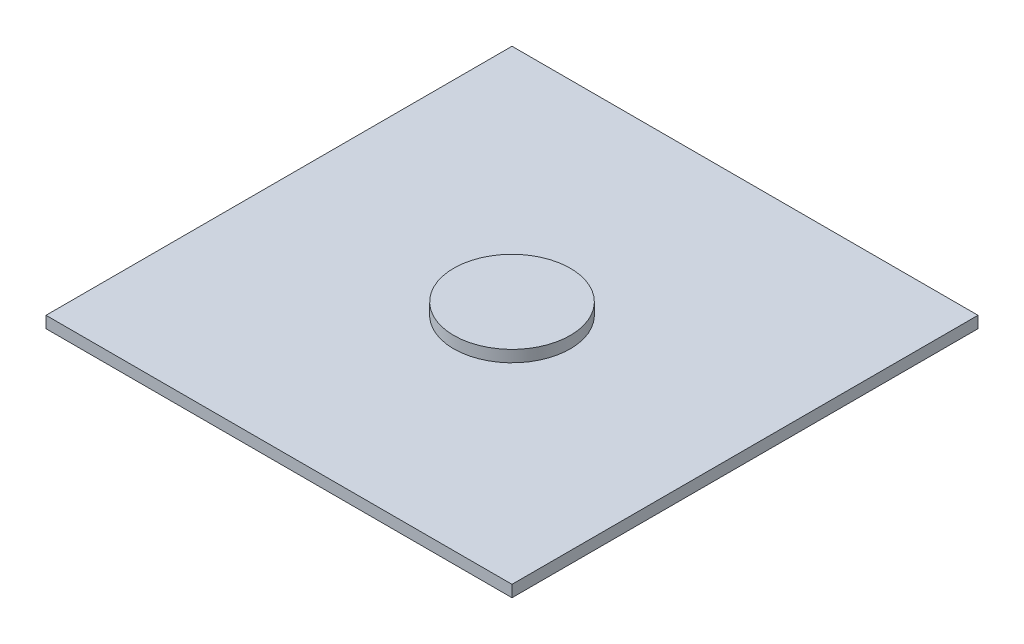
SolidWorks part; units mm, degrees
ref_plane "前视基准面" through (0, 0, 0) normal (0, 0, 1) x (1, 0, 0)
ref_plane "上视基准面" through (0, 0, 0) normal (0, 1, 0) x (1, 0, 0)
ref_plane "右视基准面" through (0, 0, 0) normal (1, 0, 0) x (0, 0, -1)
other "Configuration Table"
sketch "草图1" plane through (0, 0, 0) normal (0, 1, 0) x (1, 0, 0)
  line L1 (0, 0) -> (40, 0)
  line L2 (0, 0) -> (0, 40)
  line L3 (0, 40) -> (40, 40)
  line L4 (40, 0) -> (40, 40)
  dimension "D1" = 40
  dimension "D2" = 40
extrude "凸台-拉伸1" add sketch "草图1" along normal blind 1
sketch "草图2" plane through (0, 1, 0) normal (0, 1, 0) x (1, 0, 0)
  line L0 (0, 40) -> (40, 0) construction
  circle A0 centre (20, 20) radius 5
  point P6 (0, 0)
  dimension "D1" = 10
extrude "凸台-拉伸2" add sketch "草图2" along normal blind 1
